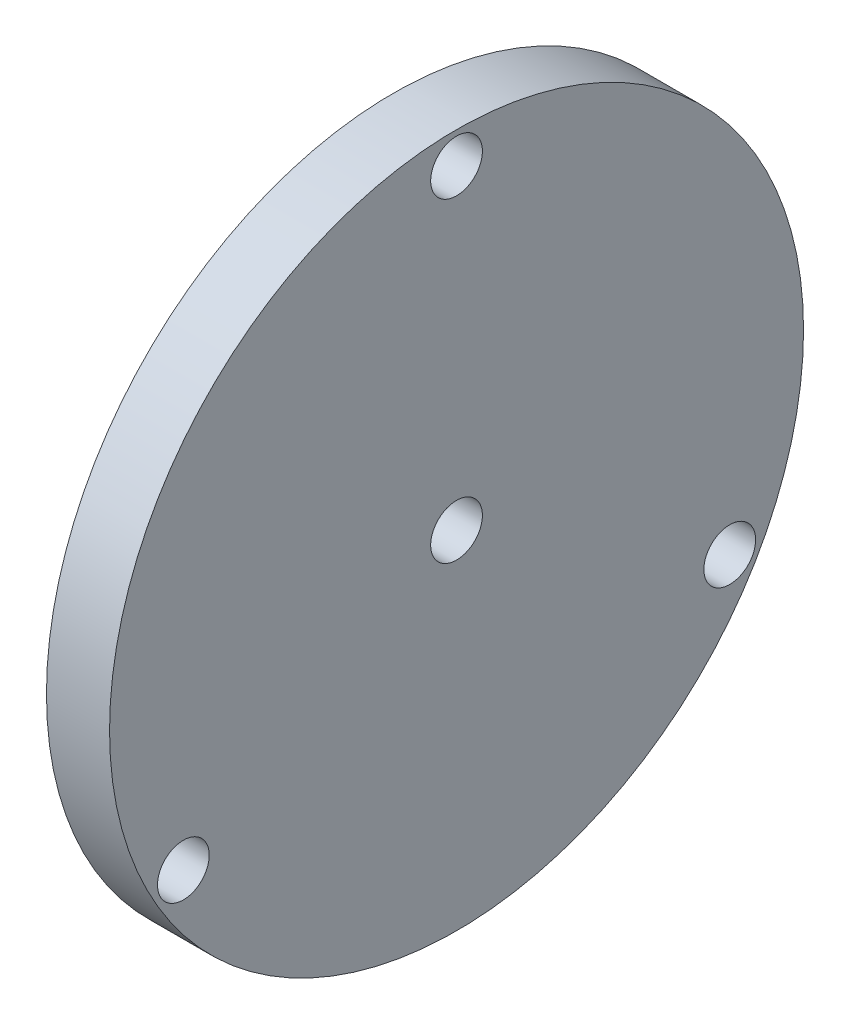
SolidWorks part; units mm, degrees
ref_plane "Ebene vorne" through (0, 0, 0) normal (0, 0, 1) x (1, 0, 0)
ref_plane "Ebene oben" through (0, 0, 0) normal (0, 1, 0) x (1, 0, 0)
ref_plane "Ebene rechts" through (0, 0, 0) normal (1, 0, 0) x (0, 0, -1)
sketch "Sketch1" plane through (0, 0, 0) normal (1, 0, 0) x (0, 0, -1)
  circle A0 centre (0, 0) radius 55
  dimension "D1" = 110
extrude "Boss-Extrude1" add sketch "Sketch1" along normal blind 10
sketch "Sketch2" plane through (0, 0, 0) normal (1, 0, 0) x (0, 0, -1)
  circle A0 centre (0, 0) radius 4.1
  circle A1 centre (0, 50) radius 4.1
  circle A2 centre (43.3013, -25) radius 4.1
  circle A3 centre (-43.3013, -25) radius 4.1
  point P12 (0, 0)
  dimension "D1" = 8.2
  dimension "D3" = 50
  dimension "D2" = 3
extrude "Cut-Extrude1" cut sketch "Sketch2" along normal through all
